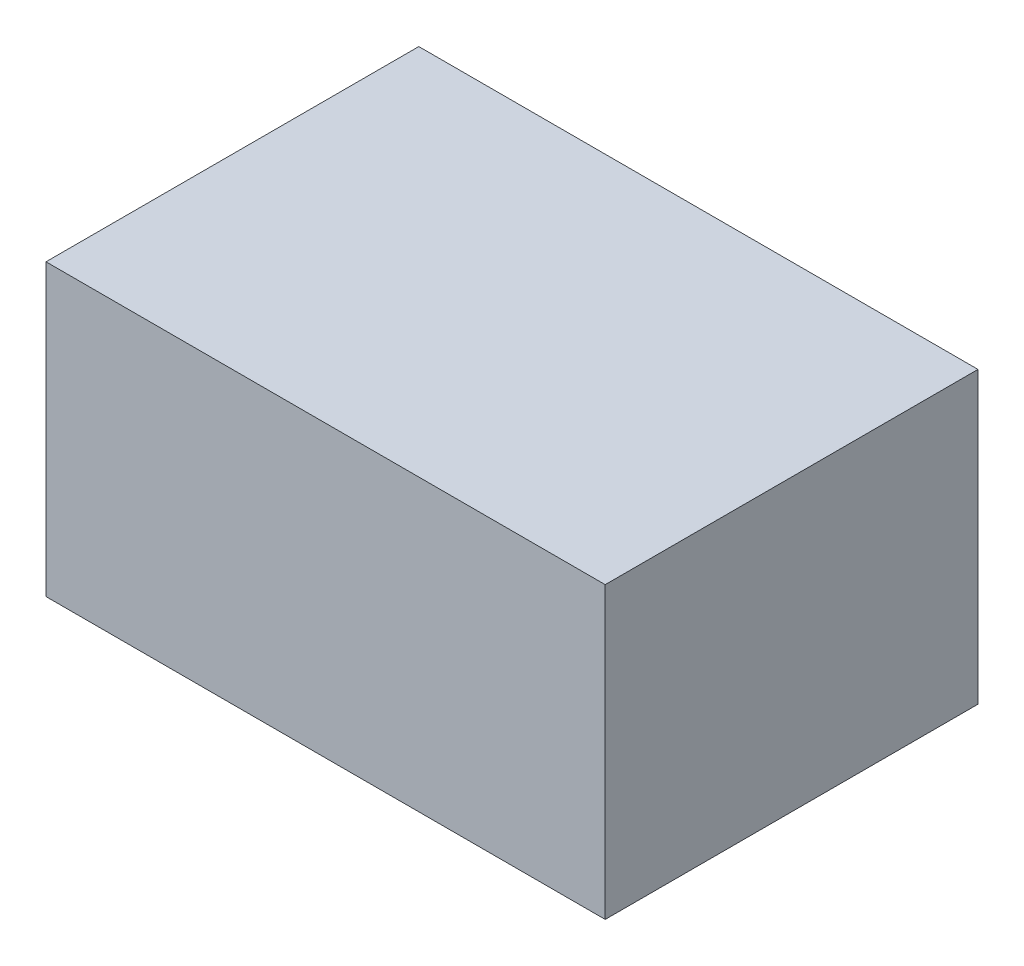
SolidWorks part; units mm, degrees
ref_plane "Płaszczyzna przednia" through (0, 0, 0) normal (0, 0, 1) x (1, 0, 0)
ref_plane "Płaszczyzna górna" through (0, 0, 0) normal (0, 1, 0) x (1, 0, 0)
ref_plane "Płaszczyzna prawa" through (0, 0, 0) normal (1, 0, 0) x (0, 0, -1)
ref_plane "Płaszczyzna1" through (31.5864, -5.35, 3.6327) normal (0, 0, 1) x (1, 0, 0)
sketch "Szkic2" plane through (0, -5.35, 0) normal (0, -1, 0) x (1, 0, 0)
  line L0 (18.0864, 3.6327) -> (31.5864, 3.6327) construction
  line L1 (18.0864, 12.6327) -> (18.0864, 3.6327) construction
  line L2 (31.5864, 12.6327) -> (18.0864, 12.6327) construction
  line L3 (31.5864, 3.6327) -> (31.5864, 12.6327) construction
  line L4 (18.0864, 3.6327) -> (31.5864, 3.6327)
  line L5 (18.0864, 12.6327) -> (18.0864, 3.6327)
  line L6 (31.5864, 12.6327) -> (18.0864, 12.6327)
  line L7 (31.5864, 3.6327) -> (31.5864, 12.6327)
extrude "Dodanie-wyciągnięcie1" add sketch "Szkic2" along normal blind 3 and the other way blind 4
